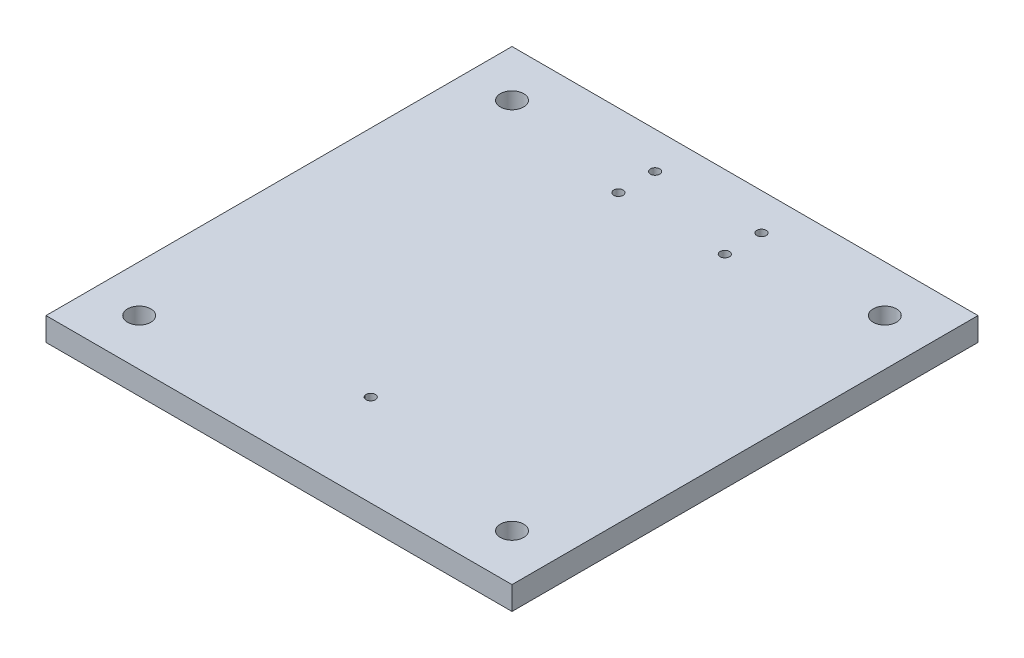
SolidWorks part; units mm, degrees
material "Brass"
ref_plane "Front Plane" through (0, 0, 0) normal (0, 0, 1) x (1, 0, 0)
ref_plane "Top Plane" through (0, 0, 0) normal (0, 1, 0) x (1, 0, 0)
ref_plane "Right Plane" through (0, 0, 0) normal (1, 0, 0) x (0, 0, -1)
sketch "Sketch1" plane through (0, 0, 0) normal (0, 1, 0) x (1, 0, 0)
  line L0 (25.4, -69.85) -> (25.4, 57.15) construction
  line L1 (-38.1, -69.85) -> (88.9, -69.85)
  line L2 (-38.1, -69.85) -> (-38.1, 57.15)
  line L3 (-38.1, 57.15) -> (88.9, 57.15)
  line L4 (88.9, -69.85) -> (88.9, 57.15)
  line L5 (-38.1, -69.85) -> (88.9, 57.15) construction
  line L6 (-38.1, 57.15) -> (88.9, -69.85) construction
  circle A0 centre (10.9, 47.15) radius 1.27
  circle A1 centre (39.9, 47.15) radius 1.27
  circle A2 centre (25.4, -44.85) radius 1.27
  circle A3 centre (10.9, 37.15) radius 1.27
  circle A4 centre (39.9, 37.15) radius 1.27
  circle A5 centre (-25.4, 44.45) radius 3.175
  circle A6 centre (76.2, 44.45) radius 3.175
  circle A7 centre (76.2, -57.15) radius 3.175
  circle A8 centre (-25.4, -57.15) radius 3.175
  point P0 (25.4, -6.35)
  dimension "D1" = 2.54
  dimension "D8" = 6.35
  dimension "D11" = 2
  dimension "D2" = 127
  dimension "D3" = 127
  dimension "D4" = 29
  dimension "D5" = 82
  dimension "D6" = 10
  dimension "D7" = 10
  dimension "D9" = 12.7
  dimension "D10" = 12.7
extrude "Boss-Extrude1" add sketch "Sketch1" along normal blind 6.35
